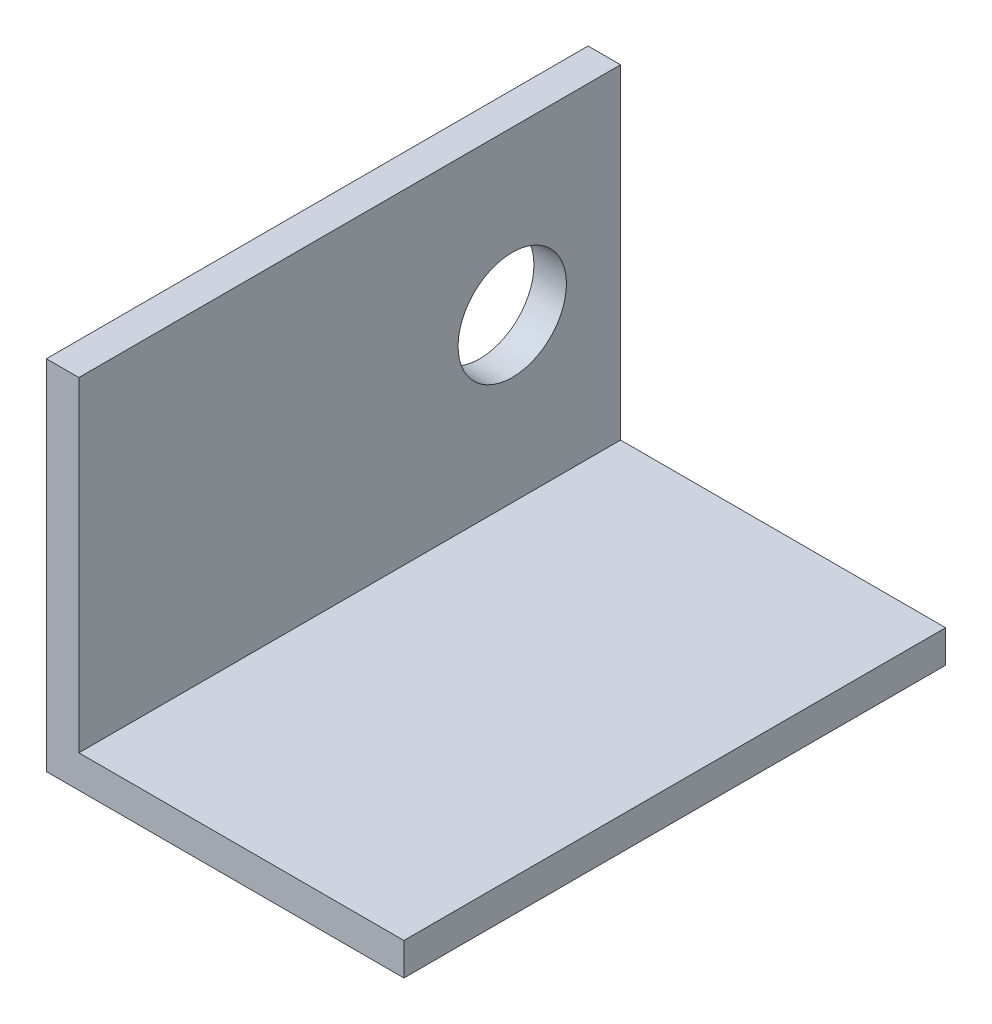
SolidWorks part; units mm, degrees
ref_plane "Спереди" through (0, 0, 0) normal (0, 0, 1) x (1, 0, 0)
ref_plane "Сверху" through (0, 0, 0) normal (0, 1, 0) x (1, 0, 0)
ref_plane "Справа" through (0, 0, 0) normal (1, 0, 0) x (0, 0, -1)
sketch "Эскиз1" plane through (0, 0, 0) normal (0, 0, 1) x (1, 0, 0)
  line L0 (0, 30) -> (0, 0)
  line L1 (0, 0) -> (30, 0)
extrude "Вытянуть-Тонкостенный1" add sketch "Эскиз1" against normal blind 50 thin
sketch "Эскиз2" plane through (-3, 0, 0) normal (-1, 0, 0) x (0, 0, 1)
  circle A0 centre (-40, 15) radius 5
extrude "Вырез-Вытянуть1" cut sketch "Эскиз2" against normal blind 10
